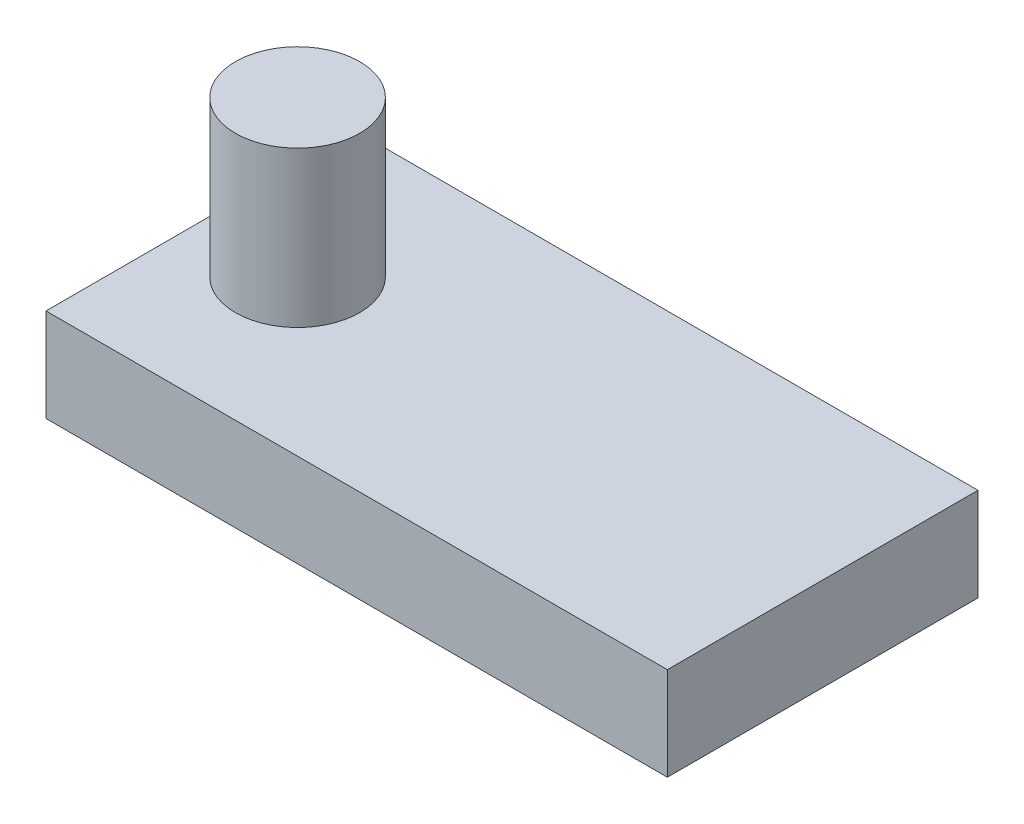
SolidWorks part; units mm, degrees
ref_plane "Front Plane" through (0, 0, 0) normal (0, 0, 1) x (1, 0, 0)
ref_plane "Top Plane" through (0, 0, 0) normal (0, 1, 0) x (1, 0, 0)
ref_plane "Right Plane" through (0, 0, 0) normal (1, 0, 0) x (0, 0, -1)
sketch "Sketch2" plane through (0, 0, 0) normal (0, 1, 0) x (1, 0, 0)
  line L1 (-25.4, 12.7) -> (25.4, 12.7)
  line L2 (-25.4, 12.7) -> (-25.4, -12.7)
  line L3 (-25.4, -12.7) -> (25.4, -12.7)
  line L4 (25.4, 12.7) -> (25.4, -12.7)
  line L5 (-25.4, 12.7) -> (25.4, -12.7) construction
  line L6 (-25.4, -12.7) -> (25.4, 12.7) construction
  point P0 (0, 0)
  dimension "D1" = 50.8
  dimension "D2" = 25.4
extrude "Boss-Extrude1" add sketch "Sketch2" along normal blind 7.62
sketch "Sketch3" plane through (0, 7.62, 0) normal (0, 1, 0) x (1, 0, 0)
  circle A0 centre (-17.5322, 0) radius 5.08
  dimension "D1" = 10.16
extrude "Boss-Extrude2" add sketch "Sketch3" along normal blind 12.7
